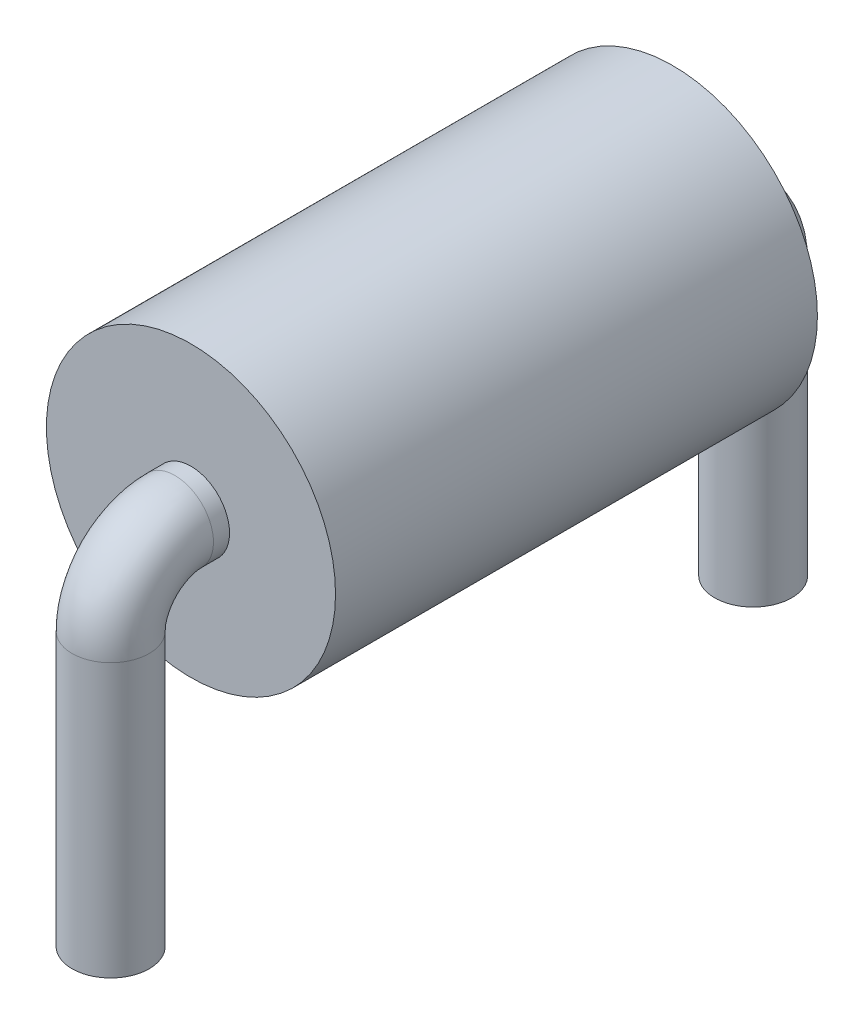
SolidWorks part; units mm, degrees
ref_plane "Спереди" through (0, 0, 0) normal (0, 0, 1) x (1, 0, 0)
ref_plane "Сверху" through (0, 0, 0) normal (0, 1, 0) x (1, 0, 0)
ref_plane "Справа" through (0, 0, 0) normal (1, 0, 0) x (0, 0, -1)
sketch "Эскиз1" plane through (0, 0, 0) normal (0, 0, 1) x (1, 0, 0)
  circle A0 centre (0, 0) radius 2.25
extrude "Бобышка-Вытянуть1" add sketch "Эскиз1" along normal mid plane 7.5
sketch "Эскиз2" plane through (0, 0, 3.75) normal (0, 0, 1) x (1, 0, 0)
  circle A0 centre (0, 0) radius 0.6
ref_plane "Плоскость1" through (0, -2.25, 0) normal (0, -1, 0) x (-1, 0, 0)
sketch "Эскиз4" plane through (0, -2.25, 0) normal (0, -1, 0) x (-1, 0, 0)
  circle A0 centre (0, -5) radius 0.6
  circle A1 centre (0, 5) radius 0.6
  point P2 (0, 0)
  point P5 (0, 0)
  dimension "D3" = 1.2
  dimension "D1" = 10
  dimension "D2" = 5
extrude "Бобышка-Вытянуть2" add sketch "Эскиз4" along normal blind 3 separate body
sketch "Эскиз5" plane through (0, 0, 0) normal (1, 0, 0) x (0, 0, -1)
  line L0 (-5, -3.4222) -> (-5, -1)
  line L7 (-4, 0) -> (-0.5257, 0)
  arc A0 (-5, -1) -> (-4, 0) centre (-4, -1) cw
  point P2 (0, 0)
  point P3 (0, 0)
  point P4 (-0.5257, 0)
  point P6 (-5, -3.4222)
  point P9 (-4, 0)
  dimension "D1" = 1
sweep "По траектории2" add profiles "Эскиз2" path "Эскиз5"
sketch "Эскиз6" plane through (0, 0, 0) normal (1, 0, 0) x (0, 0, -1)
  line L0 (5, -3.1411) -> (5, -1)
  line L1 (2.4753, 0) -> (4, 0)
  arc A0 (5, -1) -> (4, 0) centre (4, -1) ccw
  point P6 (0, 0)
  point P7 (0, 0)
  point P8 (5, -3.1411)
  point P10 (0, 0)
  point P11 (5, -2.9777)
  dimension "D1" = 1
sketch "Эскиз7" plane through (0, 0, -3.75) normal (0, 0, -1) x (-1, 0, 0)
  circle A0 centre (0, 0) radius 0.6
sweep "По траектории3" add profiles "Эскиз7" path "Эскиз6"
